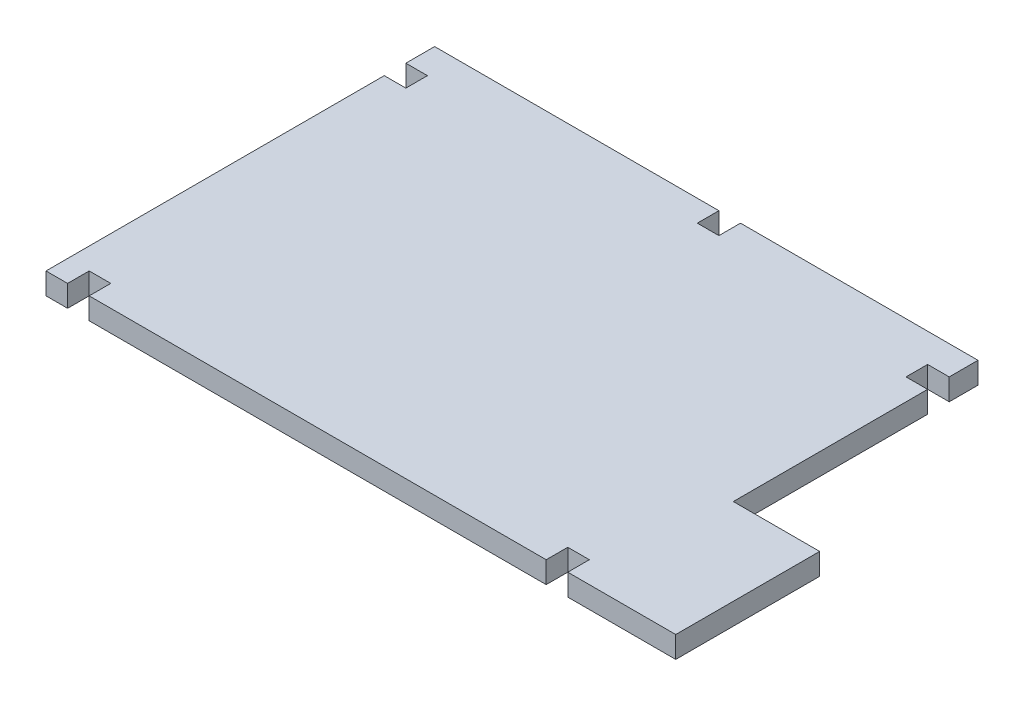
SolidWorks part; units mm, degrees
ref_plane "前视基准面" through (0, 0, 0) normal (0, 0, 1) x (1, 0, 0)
ref_plane "上视基准面" through (0, 0, 0) normal (0, 1, 0) x (1, 0, 0)
ref_plane "右视基准面" through (0, 0, 0) normal (1, 0, 0) x (0, 0, -1)
other "Configuration Table"
sketch "草图1" plane through (0, 0, 0) normal (0, 1, 0) x (1, 0, 0)
  line L0 (-67.3129, 27.6038) -> (-67.3129, 23.6038)
  line L1 (-67.3129, 23.6038) -> (-64.3129, 23.6038)
  line L2 (-64.3129, 23.6038) -> (-64.3129, 20.6038)
  line L3 (-64.3129, 20.6038) -> (-67.3129, 20.6038)
  line L4 (-67.3129, 20.6038) -> (-67.3129, -26.3962)
  line L5 (-67.3129, -26.3962) -> (-64.3129, -26.3962)
  line L6 (-64.3129, -26.3962) -> (-64.3129, -23.3962)
  line L7 (-64.3129, -23.3962) -> (-61.3129, -23.3962)
  line L8 (-61.3129, -23.3962) -> (-61.3129, -26.3962)
  line L9 (-61.3129, -26.3962) -> (2.1871, -26.3962)
  line L10 (2.1871, -26.3962) -> (2.1871, -23.3962)
  line L11 (2.1871, -23.3962) -> (5.1871, -23.3962)
  line L12 (5.1871, -23.3962) -> (5.1871, -26.3962)
  line L13 (5.1871, -26.3962) -> (20.1871, -26.3962)
  line L14 (20.1871, -26.3962) -> (20.1871, -6.3962)
  line L15 (-67.3129, 27.6038) -> (-27.8129, 27.6038)
  line L16 (-27.8129, 27.6038) -> (-27.8129, 24.6038)
  line L17 (-27.8129, 24.6038) -> (-24.8129, 24.6038)
  line L18 (-24.8129, 24.6038) -> (-24.8129, 27.6038)
  line L19 (-24.8129, 27.6038) -> (8.1871, 27.6038)
  line L20 (8.1871, 27.6038) -> (8.1871, 23.6038)
  line L21 (8.1871, 23.6038) -> (5.1871, 23.6038)
  line L22 (5.1871, 23.6038) -> (5.1871, 20.6038)
  line L23 (5.1871, 20.6038) -> (8.1871, 20.6038)
  line L24 (8.1871, 20.6038) -> (8.1871, -6.3962)
  line L25 (8.1871, -6.3962) -> (20.1871, -6.3962)
extrude "凸台-拉伸1" add sketch "草图1" along normal blind 3
